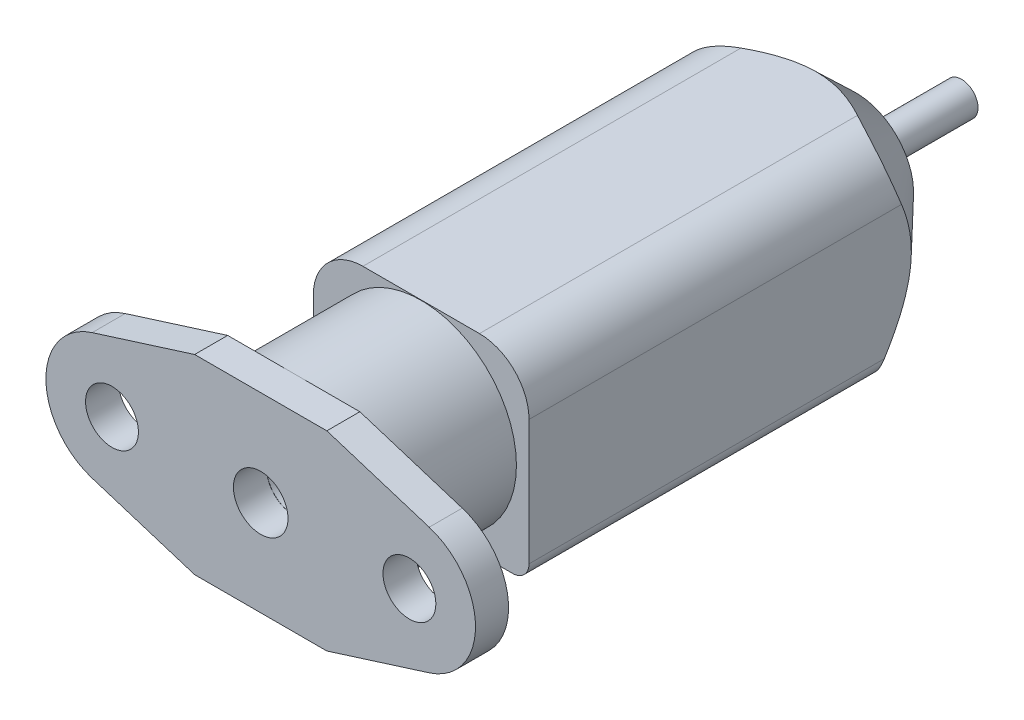
SolidWorks part; units mm, degrees
ref_plane "Alzado" through (0, 0, 0) normal (0, 0, 1) x (1, 0, 0)
ref_plane "Planta" through (0, 0, 0) normal (0, 1, 0) x (1, 0, 0)
ref_plane "Vista lateral" through (0, 0, 0) normal (1, 0, 0) x (0, 0, -1)
sketch "Croquis1" plane through (0, 0, 0) normal (0, 0, 1) x (1, 0, 0)
  line L0 (3.9898, 5.77) -> (10.1854, 3.8166)
  line L1 (-4.0102, 5.77) -> (-10.2109, 3.8161)
  line L2 (-4.0102, -5.77) -> (-10.2108, -3.8161)
  line L3 (3.9898, -5.77) -> (10.207, -3.8097)
  line L4 (3.9898, -5.77) -> (-4.0102, -5.77)
  line L5 (-4.0102, 5.77) -> (3.9898, 5.77)
  circle A0 centre (8.988, 0) radius 1.6
  circle A1 centre (-9.012, 0) radius 1.6
  circle A2 centre (-0.012, -0.0051) radius 1.6528
  arc A3 (10.207, -3.8097) -> (10.1854, 3.8166) centre (8.988, 0) ccw
  arc A4 (-10.2109, 3.8161) -> (-10.2108, -3.8161) centre (-9.012, 0) ccw
  dimension "D1" = 3.2
  dimension "D2" = 3.2
  dimension "D4" = 4
  dimension "D5" = 4
  dimension "D3" = 18
  dimension "D6" = 8
  dimension "D7" = 5.77
  dimension "D8" = 5.77
  dimension "D9" = 9
extrude "Saliente-Extruir7" add sketch "Croquis1" against normal blind 2 separate body
sketch "Croquis2" plane through (0, 0, -2) normal (0, 0, -1) x (-1, 0, 0)
  circle A0 centre (0, 0) radius 5.765
  circle A1 centre (0, 0) radius 1.6512
extrude "Saliente-Extruir8" add sketch "Croquis2" along normal blind 7.7
sketch "Croquis3" plane through (0, 0, -9.7) normal (0, 0, -1) x (-1, 0, 0)
  line L1 (3.5269, 5.7838) -> (-3.5269, 5.7838)
  line L2 (6.5269, 2.7838) -> (6.5269, -4.7838)
  line L3 (5.5269, -5.7838) -> (-5.5269, -5.7838)
  line L4 (-6.5269, 2.7838) -> (-6.5269, -4.7838)
  line L5 (6.5269, 5.7838) -> (-6.5269, -5.7838) construction
  line L6 (6.5269, -5.7838) -> (-6.5269, 5.7838) construction
  arc A0 (-3.5269, 5.7838) -> (-6.5269, 2.7838) centre (-3.5269, 2.7838) ccw
  arc A1 (3.5269, 5.7838) -> (6.5269, 2.7838) centre (3.5269, 2.7838) cw
  arc A2 (-5.5269, -5.7838) -> (-6.5269, -4.7838) centre (-5.5269, -4.7838) cw
  arc A3 (6.5269, -4.7838) -> (5.5269, -5.7838) centre (5.5269, -4.7838) cw
  point P0 (0, 0)
  dimension "D1" = 3
  dimension "D2" = 1
extrude "Saliente-Extruir9" add sketch "Croquis3" along normal blind 26.3
ref_plane "Plano1" through (0, 5.765, 0) normal (0, 1, 0) x (1, 0, 0)
ref_axis "Eje1" through (0, 0, -39.9199) along (0, 0, 1)
sketch "Croquis5" plane through (0, 0, 0) normal (0, 1, 0) x (1, 0, 0)
  line L0 (0, 36) -> (-3.5, 36) construction
  line L1 (-3.5269, 36) -> (3.5269, 36) construction
  line L2 (-3.5, 36) -> (-8.4726, 30.8035)
  line L3 (-3.5, 36) -> (-8.4726, 36)
  line L4 (-8.4726, 30.8035) -> (-8.4726, 36)
revolve "Cortar-Revolución1" cut sketch "Croquis5" angle 360 about axis through (0, 0, -39.9199) along (0, 0, 1)
sketch "Croquis6" plane through (0, 0, -36) normal (0, 0, -1) x (-1, 0, 0)
  circle A0 centre (0, 0) radius 0.9994
extrude "Saliente-Extruir10" add sketch "Croquis6" along normal blind 6.4
